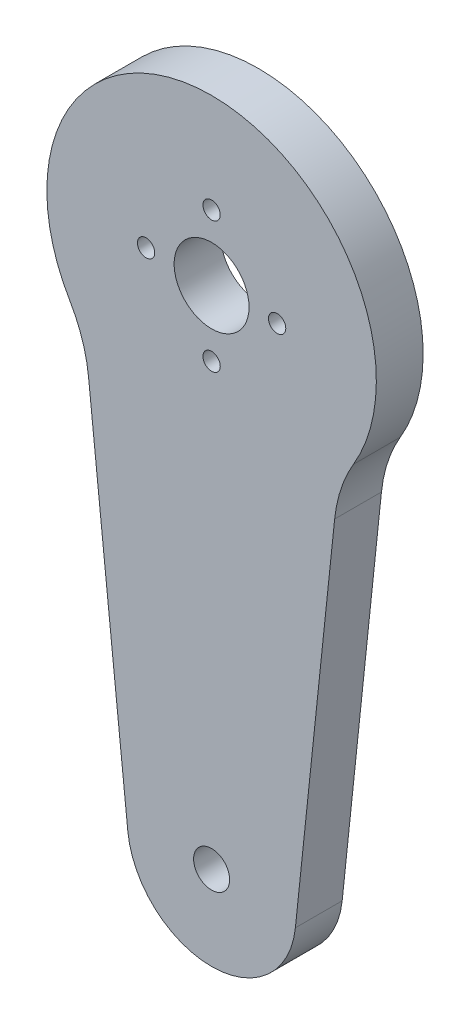
SolidWorks part; units mm, degrees
ref_plane "Plan de face" through (0, 0, 0) normal (0, 0, 1) x (1, 0, 0)
ref_plane "Plan de dessus" through (0, 0, 0) normal (0, 1, 0) x (1, 0, 0)
ref_plane "Plan de droite" through (0, 0, 0) normal (1, 0, 0) x (0, 0, -1)
sketch "Esquisse1" plane through (0, 0, 0) normal (0, 0, 1) x (1, 0, 0)
  line L0 (8.9507, -54.9408) -> (13.1466, -15.0197)
  line L1 (-13.1466, -15.0197) -> (-8.9507, -54.9408)
  line L2 (0, 0) -> (0, -54) construction
  circle A0 centre (0, 0) radius 7 construction
  arc A1 (-8.9507, -54.9408) -> (8.9507, -54.9408) centre (0, -54) ccw
  arc A2 (15.1513, -8.9553) -> (-15.1513, -8.9553) centre (0, 0) ccw
  circle A4 centre (0, -54) radius 1.925
  arc A5 (15.1513, -8.9553) -> (13.1466, -15.0197) centre (28.0644, -16.5876) ccw
  arc A6 (-13.1466, -15.0197) -> (-15.1513, -8.9553) centre (-28.0644, -16.5876) ccw
  circle A7 centre (7, 0) radius 0.925
  circle A8 centre (0, -7) radius 0.925
  circle A9 centre (0, 7) radius 0.925
  circle A10 centre (-7, 0) radius 0.925
  circle A11 centre (0, 0) radius 4
  dimension "D1" = 8
  dimension "D2" = 15
  dimension "D3" = 17.6
  dimension "D4" = 3.85
  dimension "D5" = 9
  dimension "D6" = 1.85
  dimension "D7" = 14
  dimension "D8" = 54
  dimension "D9" = 28.0644
  dimension "D10" = 28.0644
extrude "Boss.-Extru.1" add sketch "Esquisse1" along normal blind 5
